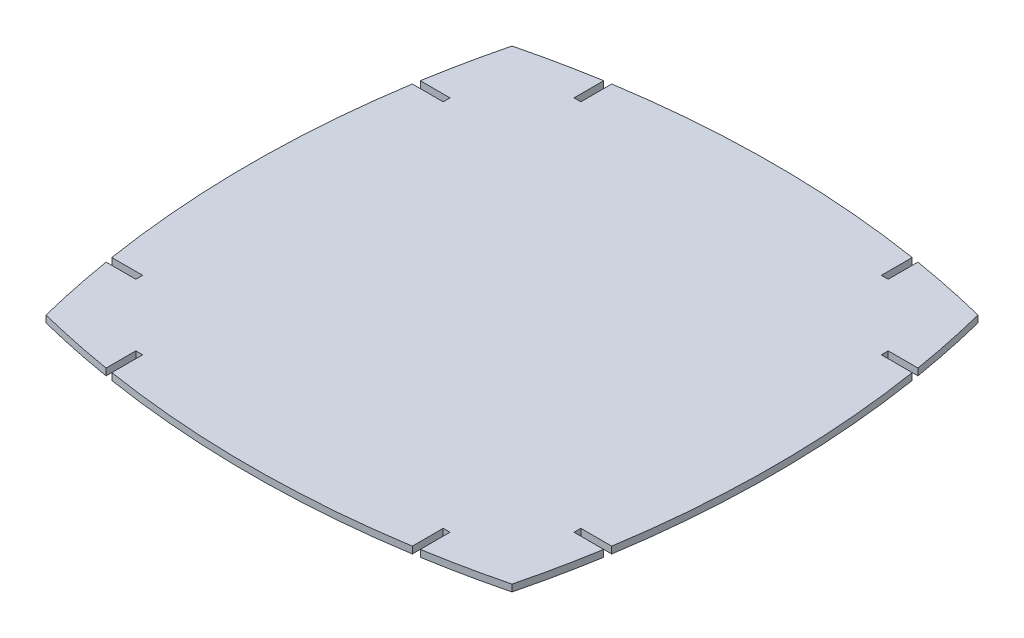
SolidWorks part; units mm, degrees
ref_plane "Front Plane" through (0, 0, 0) normal (0, 0, 1) x (1, 0, 0)
ref_plane "Top Plane" through (0, 0, 0) normal (0, 1, 0) x (1, 0, 0)
ref_plane "Right Plane" through (0, 0, 0) normal (1, 0, 0) x (0, 0, -1)
sketch "Sketch1" plane through (0, 0, 0) normal (0, 1, 0) x (1, 0, 0)
  line L0 (115, 160.4) -> (110, 160.4)
  line L1 (-170.565, 170.565) -> (170.565, 170.565) construction
  line L2 (-170.565, 170.565) -> (-170.565, -170.565) construction
  line L3 (-170.565, -170.565) -> (170.565, -170.565) construction
  line L4 (170.565, 170.565) -> (170.565, -170.565) construction
  line L5 (0, -170.565) -> (0, 170.565) construction
  line L6 (-170.565, 0) -> (170.565, 0) construction
  line L7 (-140.4, 140.4) -> (140.4, 140.4) construction
  line L8 (-140.4, 140.4) -> (-140.4, -140.4) construction
  line L9 (-140.4, -140.4) -> (140.4, -140.4) construction
  line L10 (140.4, 140.4) -> (140.4, -140.4) construction
  line L11 (0, -140.4) -> (0, 140.4) construction
  line L12 (-140.4, 0) -> (140.4, 0) construction
  line L17 (-115, 160.4) -> (-110, 160.4)
  line L18 (-115, 160.4) -> (-115, 182.1522)
  line L19 (110, 160.4) -> (110, 182.9664)
  line L20 (-110, 160.4) -> (-110, 182.9664)
  line L21 (-160.4, 115) -> (-182.1522, 115)
  line L22 (-160.4, 115) -> (-160.4, 110)
  line L23 (-160.4, 110) -> (-182.9664, 110)
  line L24 (115, 160.4) -> (115, 182.1522)
  line L29 (160.4, 115) -> (160.4, 110)
  line L30 (160.4, 115) -> (182.1522, 115)
  line L31 (160.4, 110) -> (182.9664, 110)
  line L32 (-110, -160.4) -> (-110, -182.9664)
  line L33 (-115, -160.4) -> (-115, -182.1522)
  line L34 (-115, -160.4) -> (-110, -160.4)
  line L39 (-160.4, -115) -> (-160.4, -110)
  line L40 (-160.4, -115) -> (-182.1522, -115)
  line L41 (-160.4, -110) -> (-182.9664, -110)
  line L46 (160.4, -115) -> (160.4, -110)
  line L47 (160.4, -110) -> (182.9664, -110)
  line L48 (160.4, -115) -> (182.1522, -115)
  line L49 (115, -160.4) -> (110, -160.4)
  line L50 (115, -160.4) -> (115, -182.1522)
  line L51 (110, -160.4) -> (110, -182.9664)
  arc A0 (-170.565, 170.565) -> (-115, 182.1522) centre (0, -508.3367) cw
  arc A1 (170.565, 170.565) -> (182.1522, 115) centre (-508.3367, 0) cw
  arc A2 (170.565, -170.565) -> (115, -182.1522) centre (0, 508.3367) cw
  arc A3 (-170.565, -170.565) -> (-182.1522, -115) centre (508.3367, 0) cw
  arc A4 (-110, 182.9664) -> (110, 182.9664) centre (0, -508.3367) cw
  arc A5 (-182.1522, 115) -> (-170.565, 170.565) centre (508.3367, 0) cw
  arc A6 (115, 182.1522) -> (170.565, 170.565) centre (0, -508.3367) cw
  arc A7 (182.9664, 110) -> (182.9664, -110) centre (-508.3367, 0) cw
  arc A8 (182.1522, -115) -> (170.565, -170.565) centre (-508.3367, 0) cw
  arc A9 (110, -182.9664) -> (-110, -182.9664) centre (0, 508.3367) cw
  arc A10 (-115, -182.1522) -> (-170.565, -170.565) centre (0, 508.3367) cw
  arc A11 (-182.9664, -110) -> (-182.9664, 110) centre (508.3367, 0) cw
  point P0 (0, 0)
  point P8 (0, 0)
  dimension "D2" = 700
  dimension "D1" = 341.13
  dimension "D3" = 280.8
  dimension "D4" = 25.4
  dimension "D5" = 5
  dimension "D6" = 5
  dimension "D7" = 20
  dimension "D8" = 25.4
  dimension "D9" = 20
extrude "Boss-Extrude1" add sketch "Sketch1" along normal blind 5
